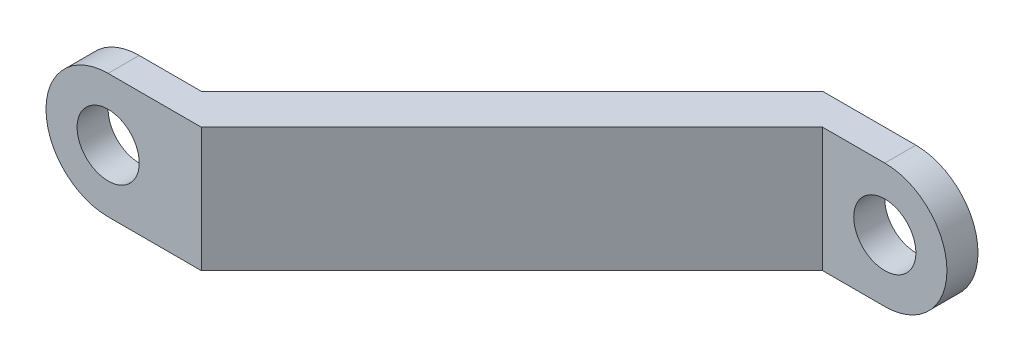
SolidWorks part; units mm, degrees
ref_plane "前视基准面" through (0, 0, 0) normal (0, 0, 1) x (1, 0, 0)
ref_plane "上视基准面" through (0, 0, 0) normal (0, 1, 0) x (1, 0, 0)
ref_plane "右视基准面" through (0, 0, 0) normal (1, 0, 0) x (0, 0, -1)
other "Configuration Table"
sketch "草图1" plane through (0, 0, 0) normal (0, 0, 1) x (1, 0, 0)
  line L0 (2.58, 5.42) -> (5.3968, 2.58) construction
  line L5 (3.9884, 0) -> (9.9884, 0)
  line L6 (9.9884, 0) -> (9.9884, 8)
  line L7 (9.9884, 8) -> (3.9884, 8)
  circle A0 centre (3.9884, 4) radius 2
  arc A1 (3.9884, 8) -> (3.9884, 0) centre (3.9884, 4) ccw
  dimension "D3" = 4
  dimension "D1" = 8
  dimension "D2" = 4
  dimension "D4" = 6
extrude "凸台-拉伸1" add sketch "草图1" along normal blind 2
sketch "草图2" plane through (0, 0, 0) normal (0, -1, 0) x (1, 0, 0)
  line L0 (9.9884, 2) -> (7.9884, 0)
  line L1 (3.9884, 0) -> (9.9884, 0) construction
  line L2 (9.9884, 2) -> (9.9884, 0) construction
  line L3 (7.9884, 0) -> (9.9884, 0)
  line L4 (9.9884, 0) -> (9.9884, 2)
  dimension "D1" = 45
extrude "切除-拉伸1" cut sketch "草图2" against normal through all
sketch "草图4" plane through (3.9942, 0, -3.9942) normal (0.7071, 0, -0.7071) x (-0.7071, 0, -0.7071)
  line L1 (-8.4771, 8) -> (-5.6486, 8)
  line L2 (-8.4771, 8) -> (-8.4771, 0)
  line L3 (-8.4771, 0) -> (-5.6486, 0)
  line L4 (-5.6486, 8) -> (-5.6486, 0)
extrude "凸台-拉伸2" add sketch "草图4" along normal blind 28.28
sketch "草图5" plane through (0, 8, 0) normal (0, 1, 0) x (1, 0, 0)
  line L0 (27.9854, 19.997) -> (27.9854, 15.997)
  line L1 (29.9854, 17.997) -> (9.9884, -2) construction
  line L2 (27.9854, 15.997) -> (29.9854, 17.997)
  line L3 (29.9854, 17.997) -> (27.9854, 19.997)
extrude "切除-拉伸2" cut sketch "草图5" against normal through all
sketch "草图6" plane through (0, 8, 0) normal (0, 1, 0) x (1, 0, 0)
  line L0 (17.9869, 9.9985) -> (23.8257, 9.9985) construction
ref_plane "基准面1" through (0, 0, -9.9985) normal (0, 0, -1) x (-1, 0, 0)
ref_plane "基准面2" through (0, 0, -19.9985) normal (0, 0, -1) x (-1, 0, 0)
sketch "草图7" plane through (0, 0, -19.9985) normal (0, 0, -1) x (-1, 0, 0)
  line L1 (-27.9854, 8) -> (-33.9854, 8)
  line L2 (-27.9854, 8) -> (-27.9854, 0)
  line L3 (-27.9854, 0) -> (-33.9854, 0)
  arc A0 (-33.9854, 8) -> (-33.9854, 0) centre (-33.9854, 4) ccw
  circle A1 centre (-33.9854, 4) radius 2
  dimension "D2" = 4
  dimension "D1" = 6
extrude "凸台-拉伸3" add sketch "草图7" against normal blind 2
sketch "草图8" plane through (0, 8, 0) normal (0, 1, 0) x (1, 0, 0)
  line L0 (27.9854, 15.997) -> (29.9869, 17.9985)
  line L1 (27.9854, 17.9985) -> (33.9854, 17.9985) construction
  line L2 (29.9869, 17.9985) -> (27.9854, 17.9985)
  line L3 (27.9854, 17.9985) -> (27.9854, 15.997)
extrude "凸台-拉伸4" add sketch "草图8" against normal up to surface (8 mm away) up to face at (20.5866, 0, -10.7988)
